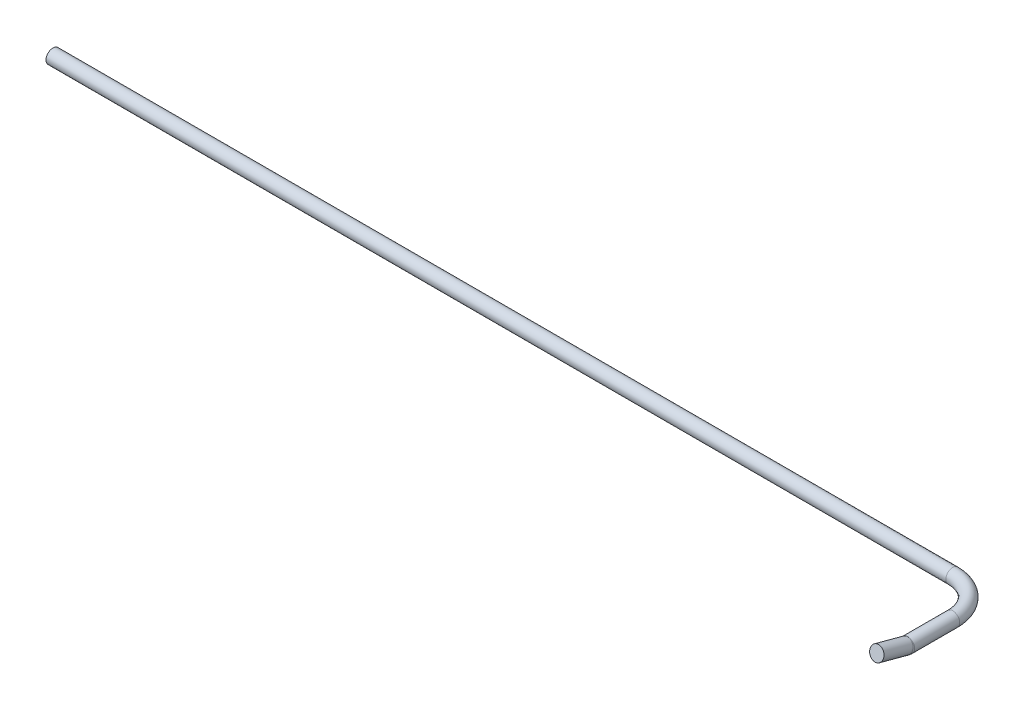
SolidWorks part; units mm, degrees
material "2024 Alloy"
ref_plane "Front Plane" through (0, 0, 0) normal (0, 0, 1) x (1, 0, 0)
ref_plane "Top Plane" through (0, 0, 0) normal (0, 1, 0) x (1, 0, 0)
ref_plane "Right Plane" through (0, 0, 0) normal (1, 0, 0) x (0, 0, -1)
sketch "Sketch1" plane through (0, 0, 0) normal (0, 0, 1) x (1, 0, 0)
  circle A0 centre (0, 0) radius 1.1811
  dimension "D1" = 2.3622
extrude "RodEnd" add sketch "Sketch1" against normal blind 7.62
sketch "Sketch2" plane through (0, 0, 0) normal (0, 0, 1) x (1, 0, 0)
  line L1 (-1.1811, -0.762) -> (1.1811, -0.762)
  line L2 (-1.1811, -0.762) -> (-1.1811, 0.762)
  line L3 (-1.1811, 0.762) -> (1.1811, 0.762)
  line L4 (1.1811, -0.762) -> (1.1811, 0.762)
  line L5 (-1.1811, -0.762) -> (1.1811, 0.762) construction
  line L6 (-1.1811, 0.762) -> (1.1811, -0.762) construction
  line L7 (-3.175, -1.1811) -> (3.175, -1.1811)
  line L8 (-3.175, -1.1811) -> (-3.175, 1.1811)
  line L9 (-3.175, 1.1811) -> (3.175, 1.1811)
  line L10 (3.175, -1.1811) -> (3.175, 1.1811)
  line L11 (-3.175, -1.1811) -> (3.175, 1.1811) construction
  line L12 (-3.175, 1.1811) -> (3.175, -1.1811) construction
  circle A0 centre (0, 0) radius 1.1811 construction
  point P0 (0, 0)
  point P8 (0, 0)
  dimension "D1" = 1.524
  dimension "D2" = 6.35
extrude "Flats" [suppressed] cut sketch "Sketch2" against normal blind 5.715
sketch "Sketch3" [suppressed] plane through (0, 0.762, 0) normal (0, 1, 0) x (1, 0, 0)
  line L0 (0.968, 0) -> (-0.968, 0) construction
  circle A0 centre (0, 1.27) radius 0.5715
  dimension "D2" = 1.143
  dimension "D1" = 1.27
extrude "Hole" [suppressed] cut sketch "Sketch3" against normal through all
sketch "Sketch4" plane through (0, 0, -7.62) normal (0, 0, -1) x (-1, 0, 0)
  line L0 (6.35, 0) -> (6.35, 2.0828) construction
  circle A0 centre (0, 0) radius 1.1811
  circle A1 centre (0, 0) radius 1.1811 construction
  dimension "D1" = 6.35
revolve "Revolve1" add sketch "Sketch4" angle 90 about L0
sketch "Sketch5" plane through (-6.35, 0, 0) normal (-1, 0, 0) x (0, 0, 1)
  circle A0 centre (-13.97, 0) radius 1.1811
  circle A1 centre (-13.97, 0) radius 1.1811 construction
extrude "Boss-Extrude1" add sketch "Sketch5" along normal blind 152.4
sketch "Sketch6" plane through (0, 0, 0) normal (0, 0, 1) x (1, 0, 0)
  line L0 (0, 1.27) -> (2.4305, 1.27) construction
  circle A0 centre (0, 0) radius 1.1811
  circle A1 centre (0, 0) radius 1.1811 construction
  dimension "D1" = 1.27
revolve "Revolve2" add sketch "Sketch6" angle 15 about L0
sketch "Sketch7" plane through (0, 0.0851, 0.3175) normal (0, 0.2588, 0.9659) x (1, 0, 0)
  circle A0 centre (0, -0.0433) radius 1.1811
  circle A1 centre (0, -0.0433) radius 1.1811 construction
extrude "Boss-Extrude2" add sketch "Sketch7" along normal blind 5.08
